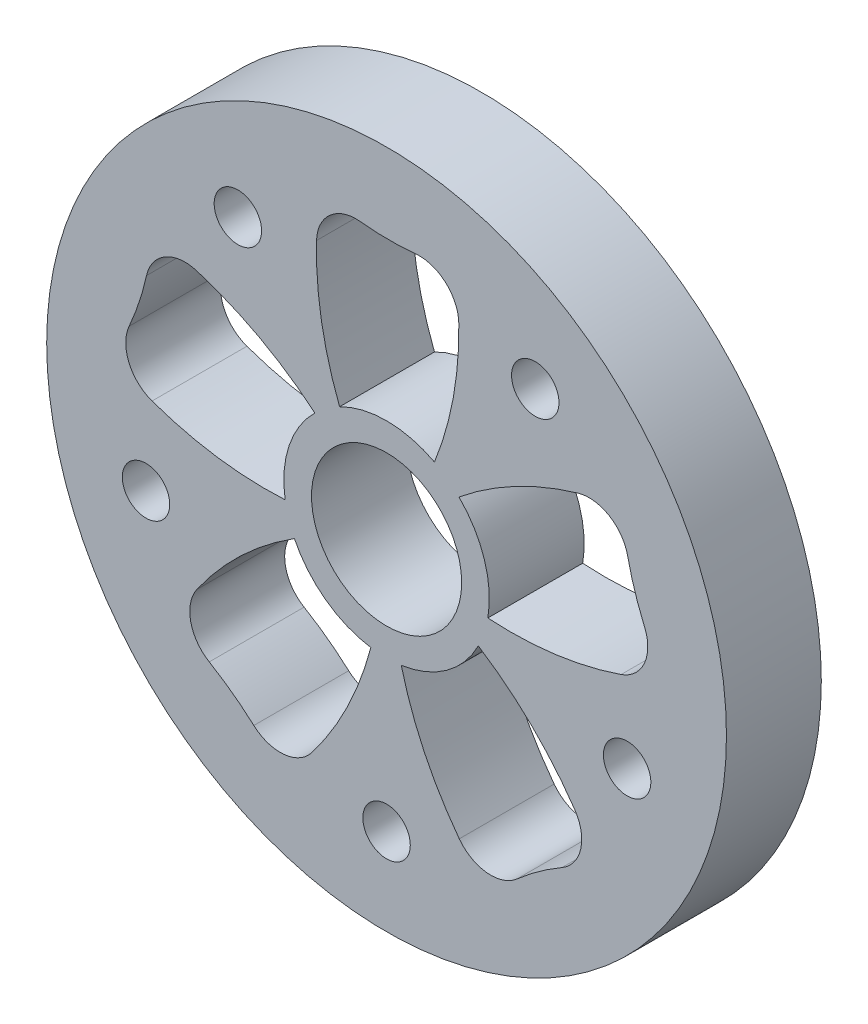
SolidWorks part; units mm, degrees
ref_plane "前视基准面" through (0, 0, 0) normal (0, 0, 1) x (1, 0, 0)
ref_plane "上视基准面" through (0, 0, 0) normal (0, 1, 0) x (1, 0, 0)
ref_plane "右视基准面" through (0, 0, 0) normal (1, 0, 0) x (0, 0, -1)
sketch "草图1" plane through (0, 0, 0) normal (0, 0, 1) x (1, 0, 0)
  line L0 (0, 0) -> (0, -49.8533) construction
  circle A0 centre (0, 0) radius 43
  circle A1 centre (0, 0) radius 32 construction
  circle A2 centre (0, 0) radius 9.5
  circle A3 centre (0, -32) radius 3
  circle A4 centre (-30.4338, -9.8885) radius 3
  circle A5 centre (-18.8091, 25.8885) radius 3
  circle A6 centre (18.8091, 25.8885) radius 3
  circle A7 centre (30.4338, -9.8885) radius 3
  point P18 (0, 0)
  dimension "D1" = 86
  dimension "D2" = 19
  dimension "D3" = 64
  dimension "D4" = 6
  dimension "D5" = 5
extrude "凸台-拉伸1" add sketch "草图1" along normal blind 12
sketch "草图2" plane through (0, 0, 12) normal (0, 0, 1) x (1, 0, 0)
  line L0 (0, 0) -> (0.2237, 44.6077) construction
  line L1 (0, 0) -> (54.1941, -2.2453) construction
  arc A0 (-9.0674, 9.3157) -> (-12.8328, -2.0783) centre (0, 0) ccw
  arc A1 (-5.9421, 11.5625) -> (-8.8569, 28.318) centre (34.1276, 27.1644) cw
  arc A2 (-8.8569, 28.318) -> (-3.3338, 33.1563) centre (-3.8587, 28.1839) cw
  arc A3 (-3.3338, 33.1563) -> (3.6661, 33.1212) centre (0.3408, 67.9628) ccw
  arc A4 (6.0577, 11.5023) -> (9.1405, 28.2278) centre (-33.8535, 27.5053) ccw
  arc A5 (9.1405, 28.2278) -> (3.6661, 33.1212) centre (4.1412, 28.1438) ccw
  arc A6 (30.5033, 13.4165) -> (32.633, 6.7483) centre (64.7418, 20.6776) ccw
  arc A7 (24.1951, 17.1742) -> (30.5033, 13.4165) centre (25.6121, 12.3792) cw
  arc A8 (9.1604, 9.2243) -> (24.1951, 17.1742) centre (36.3809, -24.063) cw
  arc A9 (12.8113, -2.2068) -> (29.6708, 0.0298) centre (15.6978, 40.6962) ccw
  arc A10 (29.6708, 0.0298) -> (32.633, 6.7483) centre (28.046, 4.7584) ccw
  arc A11 (22.1859, -24.8644) -> (16.5022, -28.9505) centre (39.6719, -55.1834) ccw
  arc A12 (23.8103, -17.7038) -> (22.1859, -24.8644) centre (19.6879, -20.5331) cw
  arc A13 (11.6035, -5.8616) -> (23.8103, -17.7038) centre (-11.6429, -42.0362) cw
  arc A14 (1.8601, -12.8662) -> (9.1971, -28.2094) centre (43.5552, -2.3537) ccw
  arc A15 (9.1971, -28.2094) -> (16.5022, -28.9505) centre (13.1922, -25.2029) ccw
  arc A16 (-16.7917, -28.7835) -> (-22.4341, -24.6407) centre (-40.2232, -54.7828) ccw
  arc A17 (-9.4795, -28.1157) -> (-16.7917, -28.7835) centre (-13.4443, -25.0694) cw
  arc A18 (-1.989, -12.8469) -> (-9.4795, -28.1157) centre (-43.5766, -1.9168) cw
  arc A19 (-11.6617, -5.7449) -> (-23.9867, -17.4641) centre (11.2208, -42.1508) ccw
  arc A20 (-23.9867, -17.4641) -> (-22.4341, -24.6407) centre (-19.8928, -20.3347) ccw
  arc A21 (-32.5637, 7.0752) -> (-30.3672, 13.7217) centre (-64.5312, 21.3257) ccw
  arc A22 (-29.669, 0.3273) -> (-32.5637, 7.0752) centre (-27.9969, 5.0394) cw
  arc A23 (-12.8328, -2.0783) -> (-29.669, 0.3273) centre (-15.2889, 40.8515) cw
  arc A24 (-9.0674, 9.3157) -> (-24.0217, 17.416) centre (-36.6204, -23.697) ccw
  arc A25 (-24.0217, 17.416) -> (-30.3672, 13.7217) centre (-25.4866, 12.6354) ccw
  arc A26 (6.0577, 11.5023) -> (-5.9421, 11.5625) centre (0, 0) ccw
  arc A27 (12.8113, -2.2068) -> (9.1604, 9.2243) centre (0, 0) ccw
  arc A28 (1.8601, -12.8662) -> (11.6035, -5.8616) centre (0, 0) ccw
  arc A29 (-11.6617, -5.7449) -> (-1.989, -12.8469) centre (0, 0) ccw
  point P11 (-15.7447, 9.3961)
  point P17 (0, 0)
  point P18 (0, 0)
  point P63 (0, 0)
  point P64 (0, 0)
  point P65 (-5.9421, 11.5023)
  dimension "D1" = 26
  dimension "D3" = 43
  dimension "D4" = 5
  dimension "D2" = 28
  dimension "D5" = 8
  dimension "D6" = 12
  dimension "D7" = 7
  dimension "D8" = 5
extrude "切除-拉伸1" cut sketch "草图2" against normal through all
